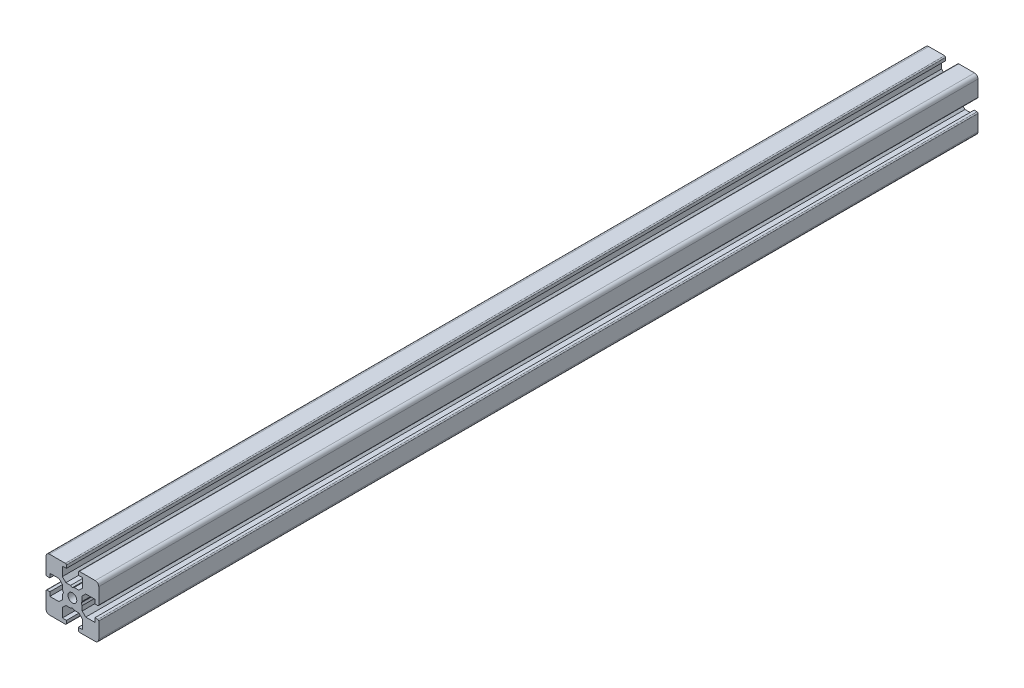
SolidWorks part; units mm, degrees
ref_plane "Front" through (0, 0, 0) normal (0, 0, 1) x (1, 0, 0)
ref_plane "Top" through (0, 0, 0) normal (0, 1, 0) x (1, 0, 0)
ref_plane "Right" through (0, 0, 0) normal (1, 0, 0) x (0, 0, -1)
ref_plane "Plane1" through (0, 0, 300) normal (0, 0, 1) x (1, 0, 0)
sketch "Sketch1" plane through (0, 0, 300) normal (0, 0, 1) x (1, 0, 0)
  line L0 (-7.5, 6.5) -> (-7.5, 2)
  line L1 (-7.2, 1.7) -> (-6.4, 1.7)
  line L2 (-6.4, 1.7) -> (-6.4, 2.85)
  line L3 (-6.4, 2.85) -> (-3.8, 2.85)
  line L4 (-3.8, 2.85) -> (-2.8, 1.85)
  line L5 (-2.8, 1.85) -> (-2.8, 0.5196)
  line L6 (-2.8, 0.5196) -> (-2.5, 0)
  line L7 (-2.5, 0) -> (-2.8, -0.5196)
  line L8 (-2.8, -0.5196) -> (-2.8, -1.85)
  line L9 (-2.8, -1.85) -> (-3.8, -2.85)
  line L10 (-3.8, -2.85) -> (-6.4, -2.85)
  line L11 (-6.4, -2.85) -> (-6.4, -1.7)
  line L12 (-6.4, -1.7) -> (-7.2, -1.7)
  line L13 (-7.5, -2) -> (-7.5, -6.5)
  line L14 (-6.5, -7.5) -> (-2, -7.5)
  line L15 (-1.7, -7.2) -> (-1.7, -6.4)
  line L16 (-1.7, -6.4) -> (-2.85, -6.4)
  line L17 (-2.85, -6.4) -> (-2.85, -3.8)
  line L18 (-2.85, -3.8) -> (-1.85, -2.8)
  line L19 (-1.85, -2.8) -> (-0.5196, -2.8)
  line L20 (-0.5196, -2.8) -> (0, -2.5)
  line L21 (0, -2.5) -> (0.5196, -2.8)
  line L22 (0.5196, -2.8) -> (1.85, -2.8)
  line L23 (1.85, -2.8) -> (2.85, -3.8)
  line L24 (2.85, -3.8) -> (2.85, -6.4)
  line L25 (2.85, -6.4) -> (1.7, -6.4)
  line L26 (1.7, -6.4) -> (1.7, -7.2)
  line L27 (2, -7.5) -> (6.5, -7.5)
  line L28 (7.5, -6.5) -> (7.5, -2)
  line L29 (7.2, -1.7) -> (6.4, -1.7)
  line L30 (6.4, -1.7) -> (6.4, -2.85)
  line L31 (6.4, -2.85) -> (3.8, -2.85)
  line L32 (3.8, -2.85) -> (2.8, -1.85)
  line L33 (2.8, -1.85) -> (2.8, -0.5196)
  line L34 (2.8, -0.5196) -> (2.5, 0)
  line L35 (2.5, 0) -> (2.8, 0.5196)
  line L36 (2.8, 0.5196) -> (2.8, 1.85)
  line L37 (2.8, 1.85) -> (3.8, 2.85)
  line L38 (3.8, 2.85) -> (6.4, 2.85)
  line L39 (6.4, 2.85) -> (6.4, 1.7)
  line L40 (6.4, 1.7) -> (7.2, 1.7)
  line L41 (7.5, 2) -> (7.5, 6.5)
  line L42 (6.5, 7.5) -> (2, 7.5)
  line L43 (1.7, 7.2) -> (1.7, 6.4)
  line L44 (1.7, 6.4) -> (2.85, 6.4)
  line L45 (2.85, 6.4) -> (2.85, 3.8)
  line L46 (2.85, 3.8) -> (1.85, 2.8)
  line L47 (1.85, 2.8) -> (0.5196, 2.8)
  line L48 (0.5196, 2.8) -> (0, 2.5)
  line L49 (0, 2.5) -> (-0.5196, 2.8)
  line L50 (-0.5196, 2.8) -> (-1.85, 2.8)
  line L51 (-1.85, 2.8) -> (-2.85, 3.8)
  line L52 (-2.85, 3.8) -> (-2.85, 6.4)
  line L53 (-2.85, 6.4) -> (-1.7, 6.4)
  line L54 (-1.7, 6.4) -> (-1.7, 7.2)
  line L55 (-2, 7.5) -> (-6.5, 7.5)
  circle A0 centre (0, 0) radius 1.25
  arc A1 (-7.5, 2) -> (-7.2, 1.7) centre (-7.2, 2) ccw
  arc A2 (-7.2, -1.7) -> (-7.5, -2) centre (-7.2, -2) ccw
  arc A3 (-7.5, -6.5) -> (-6.5, -7.5) centre (-6.5, -6.5) ccw
  arc A4 (-2, -7.5) -> (-1.7, -7.2) centre (-2, -7.2) ccw
  arc A5 (1.7, -7.2) -> (2, -7.5) centre (2, -7.2) ccw
  arc A6 (6.5, -7.5) -> (7.5, -6.5) centre (6.5, -6.5) ccw
  arc A7 (7.5, -2) -> (7.2, -1.7) centre (7.2, -2) ccw
  arc A8 (7.2, 1.7) -> (7.5, 2) centre (7.2, 2) ccw
  arc A9 (7.5, 6.5) -> (6.5, 7.5) centre (6.5, 6.5) ccw
  arc A10 (2, 7.5) -> (1.7, 7.2) centre (2, 7.2) ccw
  arc A11 (-1.7, 7.2) -> (-2, 7.5) centre (-2, 7.2) ccw
  arc A12 (-6.5, 7.5) -> (-7.5, 6.5) centre (-6.5, 6.5) ccw
extrude "Boss-Extrude1" add sketch "Sketch1" against normal blind 250
